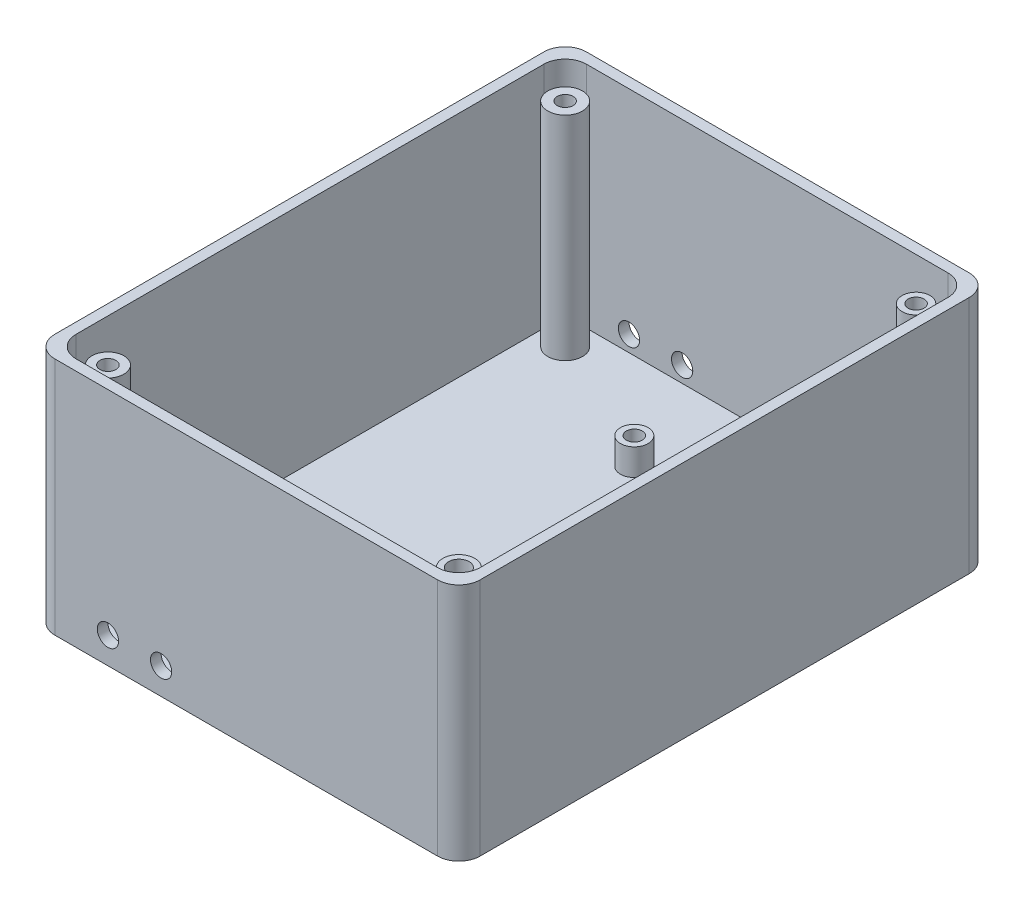
SolidWorks part; units mm, degrees
ref_plane "Front Plane" through (0, 0, 0) normal (0, 0, 1) x (1, 0, 0)
ref_plane "Top Plane" through (0, 0, 0) normal (0, 1, 0) x (1, 0, 0)
ref_plane "Right Plane" through (0, 0, 0) normal (1, 0, 0) x (0, 0, -1)
sketch "Sketch1" plane through (0, 0, 0) normal (0, 1, 0) x (1, 0, 0)
  line L1 (-40, 50) -> (40, 50)
  line L2 (-40, 50) -> (-40, -50)
  line L3 (-40, -50) -> (40, -50)
  line L4 (40, 50) -> (40, -50)
  line L5 (-40, 50) -> (40, -50) construction
  line L6 (-40, -50) -> (40, 50) construction
  point P0 (0, 0)
  dimension "D1" = 80
  dimension "D2" = 100
extrude "Boss-Extrude1" add sketch "Sketch1" along normal blind 45
shell "Shell1" thickness 2
fillet "Fillet1" radius 4 1 edges at (-40, 22.5, 50)
fillet "Fillet2" radius 4 1 edges at (-38, 23.5, 48)
fillet "Fillet4" radius 4 1 edges at (-38, 23.5, -48)
fillet "Fillet5" radius 4 1 edges at (-40, 22.5, -50)
fillet "Fillet6" radius 4 1 edges at (38, 23.5, 48)
fillet "Fillet7" radius 4 1 edges at (40, 22.5, 50)
fillet "Fillet12" radius 4 1 edges at (40, 22.5, -50)
fillet "Fillet13" radius 4 1 edges at (38, 23.5, -48)
sketch "Sketch33" plane through (0, 2, 0) normal (0, 1, 0) x (1, 0, 0)
  line L0 (38, -44) -> (38, 44) construction
  line L1 (34, 48) -> (-34, 48) construction
  line L2 (-34, -48) -> (34, -48) construction
  circle A0 centre (28, 30) radius 2.6
  circle A1 centre (28, -30) radius 2.6
  circle A2 centre (-7, 30) radius 2.6
  circle A3 centre (-7, -30) radius 2.6
  point P0 (28, 30)
  point P1 (-7, 30)
  point P2 (-7, -30)
  point P3 (28, -30)
  dimension "D1" = 10
  dimension "D2" = 10
  dimension "D3" = 60
  dimension "D4" = 18
  dimension "D5" = 18
  dimension "D6" = 18
  dimension "D7" = 18
  dimension "D8" = 35
  dimension "D9" = 35
extrude "Boss-Extrude9" add sketch "Sketch33" along normal blind 5 contours A2 | A1 | A0 | A3
sketch "Sketch37" plane through (0, 2, 0) normal (0, 1, 0) x (1, 0, 0)
  line L0 (38, -44) -> (38, 44) construction
  line L1 (34, 48) -> (-34, 48) construction
  line L2 (-38, 44) -> (-38, -44) construction
  line L4 (-34, -48) -> (34, -48) construction
  circle A0 centre (33, 43) radius 2.6244
  circle A1 centre (33, -43) radius 3
  circle A2 centre (-33, 43) radius 3.2643
  circle A3 centre (-33, -43) radius 3
  point P0 (33, -43)
  point P1 (33, 43)
  point P2 (-33, 43)
  point P3 (-33, -43)
  dimension "D1" = 5
  dimension "D2" = 5
  dimension "D3" = 5
  dimension "D4" = 5
  dimension "D5" = 5
  dimension "D6" = 5
  dimension "D7" = 5
  dimension "D8" = 5
extrude "Boss-Extrude10" add sketch "Sketch37" along normal blind 40
sketch "Sketch38" plane through (0, 42, 0) normal (0, 1, 0) x (1, 0, 0)
  circle A0 centre (33, 43) radius 1.5
  circle A1 centre (33, -43) radius 1.9383
  circle A3 centre (-33, 43) radius 1.5
  circle A4 centre (-33, -43) radius 1.5
extrude "Cut-Extrude3" cut sketch "Sketch38" against normal blind 40 contours A1 | A4 | A3 | A0
sketch "Sketch39" plane through (0, 7, 0) normal (0, 1, 0) x (1, 0, 0)
  circle A0 centre (28, 30) radius 1.5
  circle A1 centre (28, -30) radius 1.5
  circle A2 centre (-7, 30) radius 1.5
  circle A3 centre (-7, -30) radius 1.5
extrude "Cut-Extrude4" cut sketch "Sketch39" against normal blind 5
sketch "Sketch40" plane through (0, 0, 50) normal (0, 0, 1) x (1, 0, 0)
  line L0 (-36, 0) -> (36, 0) construction
  line L1 (-36, 45) -> (-36, 0) construction
  circle A0 centre (-26, 5) radius 2
  circle A1 centre (-16, 5) radius 2
  dimension "D1" = 5
  dimension "D3" = 5
  dimension "D2" = 10
  dimension "D4" = 10
sketch "Sketch41" plane through (0, 0, -50) normal (0, 0, -1) x (-1, 0, 0)
  circle A0 centre (26, 5) radius 2
  circle A1 centre (16, 5) radius 2
  dimension "D1" = 10
extrude "Cut-Extrude5" cut sketch "Sketch40" against normal blind 10 contours A1 | A0
extrude "Cut-Extrude6" cut sketch "Sketch41" against normal blind 10 contours A0 | A1
sketch "Sketch44" plane through (0, 0, 50) normal (0, 0, 1) x (1, 0, 0)
  text T0 "Power"
sketch "Sketch45" plane through (0, 0, -50) normal (0, 0, -1) x (-1, 0, 0)
  text T0 "LED Out"
equation "\"0.8cmcm\"=0.2"
